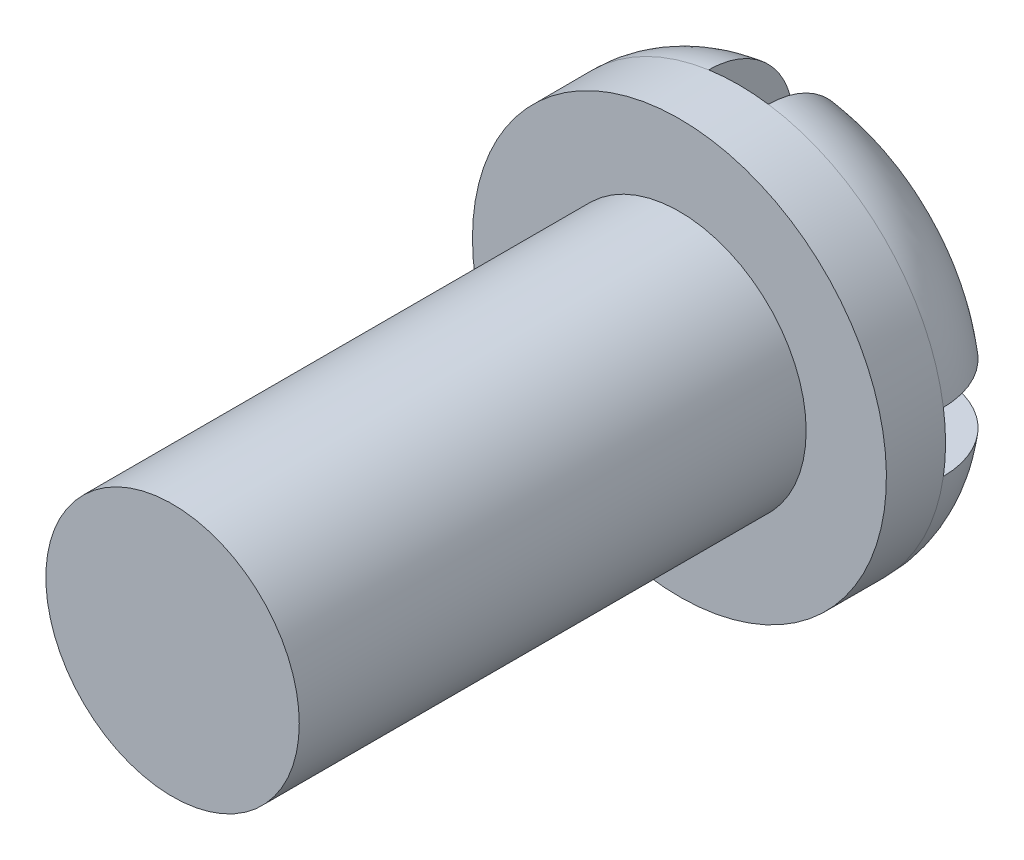
SolidWorks part; units mm, degrees
ref_plane "前视基准面" through (0, 0, 0) normal (0, 0, 1) x (1, 0, 0)
ref_plane "上视基准面" through (0, 0, 0) normal (0, 1, 0) x (1, 0, 0)
ref_plane "右视基准面" through (0, 0, 0) normal (1, 0, 0) x (0, 0, -1)
sketch "草图1" plane through (0, 0, 0) normal (0, 0, 1) x (1, 0, 0)
  circle A0 centre (0, 0) radius 3
extrude "凸台-拉伸1" add sketch "草图1" along normal blind 12
sketch "草图2" plane through (0, 0, 0) normal (0, 0, -1) x (-1, 0, 0)
  circle A0 centre (0, 0) radius 4.9
  dimension "D1" = 9.8
extrude "凸台-拉伸2" add sketch "草图2" along normal blind 3.4
fillet "圆角1" radius 2 1 edges at (-4.9, 0, -3.4)
sketch "草图3" plane through (0, 0, -3.4) normal (0, 0, -1) x (-1, 0, 0)
  line L0 (-0.7071, 0.7071) -> (-0.7071, 6.0064)
  line L1 (1, -1) -> (-1, -1) construction
  line L2 (1, -1) -> (1, 1) construction
  line L3 (1, 1) -> (-1, 1) construction
  line L4 (-1, -1) -> (-1, 1) construction
  line L5 (1, -1) -> (-1, 1) construction
  line L6 (1, 1) -> (-1, -1) construction
  line L7 (0.7071, 0.7071) -> (0.7071, 6.0064)
  line L8 (0.7071, 6.0064) -> (-0.7071, 6.0064)
  line L9 (0.7071, 0.7071) -> (6.0064, 0.7071)
  line L10 (0.7071, -0.7071) -> (6.0064, -0.7071)
  line L11 (6.0064, -0.7071) -> (6.0064, 0.7071)
  line L12 (0.7071, -0.7071) -> (0.7071, -6.0064)
  line L13 (-0.7071, -0.7071) -> (-0.7071, -6.0064)
  line L14 (-0.7071, -6.0064) -> (0.7071, -6.0064)
  line L15 (-0.7071, -0.7071) -> (-6.0064, -0.7071)
  line L16 (-0.7071, 0.7071) -> (-6.0064, 0.7071)
  line L17 (-6.0064, 0.7071) -> (-6.0064, -0.7071)
  circle A0 centre (0, 0) radius 1 construction
  dimension "D1" = 4
extrude "切除-拉伸1" cut sketch "草图3" against normal blind 2
